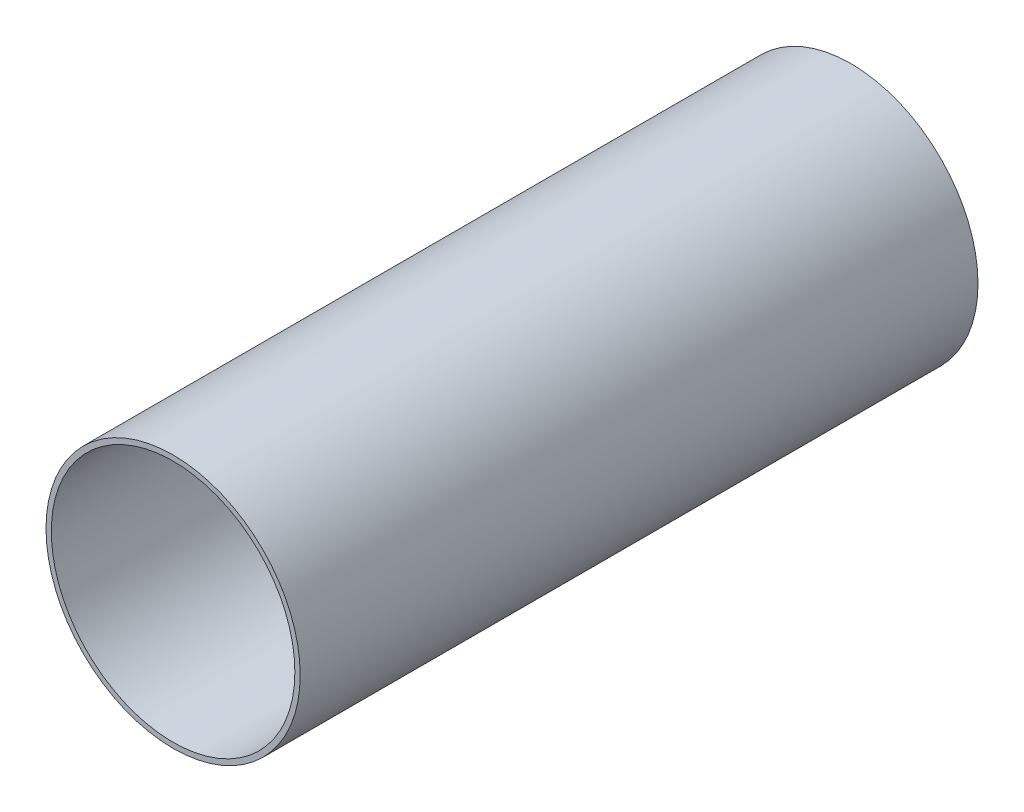
SolidWorks part; units mm, degrees
ref_plane "Front Plane" through (0, 0, 0) normal (0, 0, 1) x (1, 0, 0)
ref_plane "Top Plane" through (0, 0, 0) normal (0, 1, 0) x (1, 0, 0)
ref_plane "Right Plane" through (0, 0, 0) normal (1, 0, 0) x (0, 0, -1)
sketch "Sketch1" plane through (0, 0, 0) normal (0, 0, 1) x (1, 0, 0)
  circle A0 centre (0, 0) radius 38.1
  circle A1 centre (0, 0) radius 36.5125
  dimension "D1" = 76.2
  dimension "D2" = 73.025
extrude "Boss-Extrude1" add sketch "Sketch1" along normal blind 203.2
